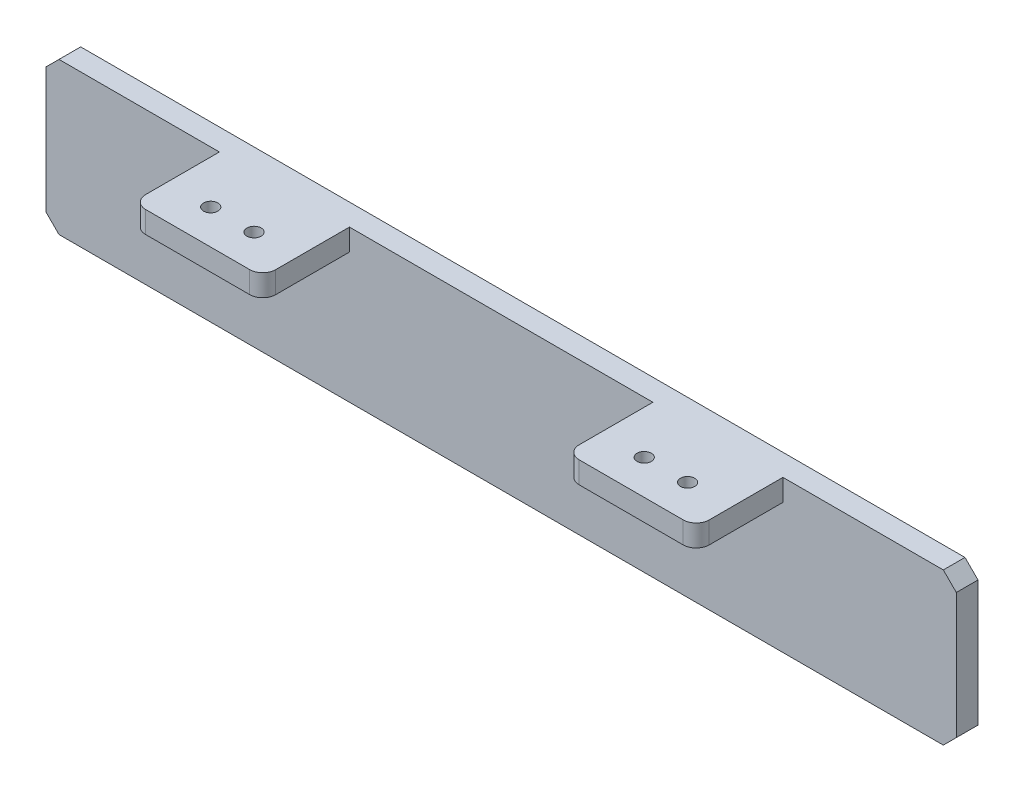
SolidWorks part; units mm, degrees
ref_plane "前视基准面" through (0, 0, 0) normal (0, 0, 1) x (1, 0, 0)
ref_plane "上视基准面" through (0, 0, 0) normal (0, 1, 0) x (1, 0, 0)
ref_plane "右视基准面" through (0, 0, 0) normal (1, 0, 0) x (0, 0, -1)
sketch "草图1" plane through (0, 0, 0) normal (0, 0, 1) x (1, 0, 0)
  line L1 (0, 0) -> (210, 0)
  line L2 (0, 0) -> (0, 35)
  line L3 (0, 35) -> (210, 35)
  line L4 (210, 0) -> (210, 35)
  dimension "D1" = 210
  dimension "D2" = 35
extrude "凸台-拉伸1" add sketch "草图1" along normal blind 5
sketch "草图2" plane through (0, 0, 5) normal (0, 0, 1) x (1, 0, 0)
  line L0 (210, 35) -> (0, 35) construction
  line L1 (40, 35) -> (70, 35)
  line L2 (40, 35) -> (40, 30)
  line L3 (40, 30) -> (70, 30)
  line L4 (70, 35) -> (70, 30)
  line L5 (0, 35) -> (0, 0) construction
  line L6 (140, 35) -> (170, 35)
  line L7 (140, 35) -> (140, 30)
  line L8 (140, 30) -> (170, 30)
  line L9 (170, 35) -> (170, 30)
  line L10 (210, 0) -> (210, 35) construction
  dimension "D1" = 5
  dimension "D2" = 5
  dimension "D3" = 40
  dimension "D4" = 40
  dimension "D5" = 70
extrude "凸台-拉伸2" add sketch "草图2" along normal blind 20
sketch "草图3" plane through (0, 35, 0) normal (0, 1, 0) x (1, 0, 0)
  line L1 (170, -25) -> (140, -25) construction
  line L3 (70, -25) -> (40, -25) construction
  line L4 (55, -25) -> (55, 0) construction
  line L5 (210, 0) -> (0, 0) construction
  line L6 (155, -25) -> (155, 0) construction
  circle A0 centre (160, -17) radius 1.65
  circle A1 centre (150, -17) radius 1.65
  circle A2 centre (60, -17) radius 1.65
  circle A3 centre (50, -17) radius 1.65
  point P18 (0, 0)
  dimension "D1" = 10
  dimension "D3" = 3.3
  dimension "D7" = 3.3
  dimension "D2" = 3.3
  dimension "D6" = 8
  dimension "D9" = 10
  dimension "D11" = 8
extrude "切除-拉伸1" cut sketch "草图3" against normal blind 10
fillet "圆角1" radius 3 4 edges at (140, 32.5, 25) (40, 32.5, 25) (170, 32.5, 25) (70, 32.5, 25)
chamfer "倒角1" distance 3 angle 45 4 edges at (0, 0, 2.5) (0, 35, 2.5) (210, 0, 2.5) (210, 35, 2.5)
